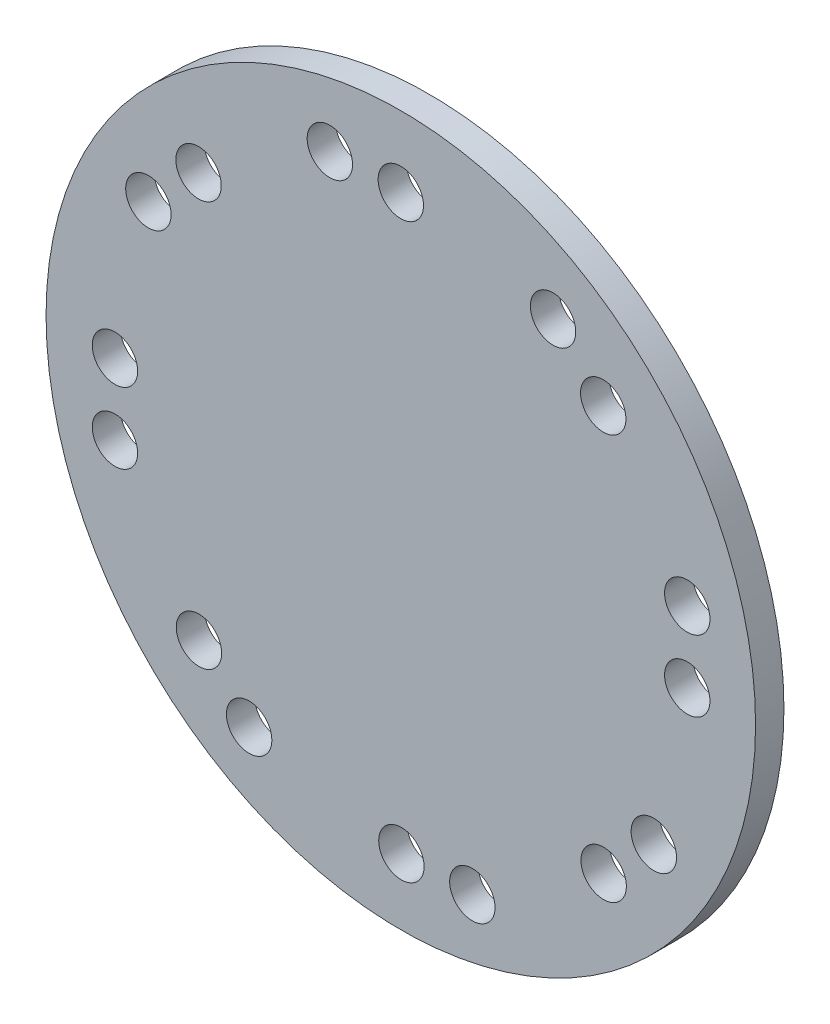
SolidWorks part; units mm, degrees
ref_plane "正面" through (0, 0, 0) normal (0, 0, 1) x (1, 0, 0)
ref_plane "平面" through (0, 0, 0) normal (0, 1, 0) x (1, 0, 0)
ref_plane "右側面" through (0, 0, 0) normal (1, 0, 0) x (0, 0, -1)
sketch "ｽｹｯﾁ1" plane through (0, 0, 0) normal (0, 0, 1) x (1, 0, 0)
  circle A0 centre (0, 0) radius 25
  dimension "D1" = 50
extrude "ﾎﾞｽ - 押し出し1" add sketch "ｽｹｯﾁ1" along normal blind 2
sketch "ｽｹｯﾁ2" plane through (0, 0, 2) normal (0, 0, 1) x (1, 0, 0)
  line L0 (0, 25) -> (0, -25) construction
  line L1 (0, 20) -> (-5, 20) construction
  circle A0 centre (0, 0) radius 25 construction
  circle A1 centre (0, 20) radius 1.6
  circle A2 centre (-5, 20) radius 1.6
  point P9 (0, 0)
  point P11 (0, 0)
  point P12 (-3.94, 16.9216)
  dimension "D2" = 5
  dimension "D3" = 3.2
  dimension "D1" = 90
  dimension "D4" = 20
extrude "ｶｯﾄ - 押し出し1" cut sketch "ｽｹｯﾁ2" against normal blind 2
pattern_circular "円形ﾊﾟﾀｰﾝ1" count 8 over 360 about axis through (0.0206, -0.1652, 0) along (0, 0, 1) of "ｶｯﾄ - 押し出し1"
